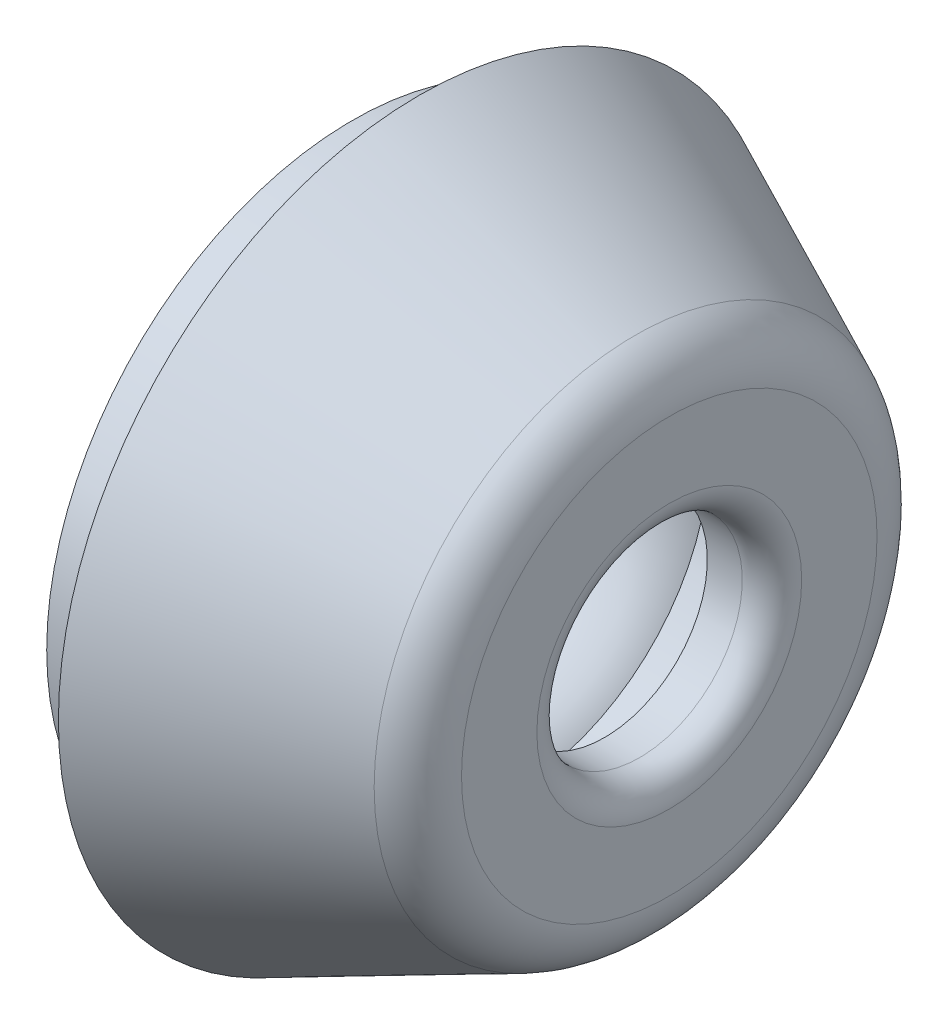
SolidWorks part; units mm, degrees
ref_plane "Face" through (0, 0, 0) normal (0, 0, 1) x (1, 0, 0)
ref_plane "Dessus" through (0, 0, 0) normal (0, 1, 0) x (1, 0, 0)
ref_plane "Droite" through (0, 0, 0) normal (1, 0, 0) x (0, 0, -1)
sketch "Esquisse1" plane through (0, 0, 0) normal (0, 0, 1) x (1, 0, 0)
  line L0 (98.1826, 9.8987) -> (98.1826, 15.4534)
  line L1 (81.0486, 0) -> (115.9484, 0) construction
  line L2 (98.1826, 15.4534) -> (101.5582, 15.4534)
  line L3 (101.5582, 15.4534) -> (101.5582, 18.2382)
  line L4 (101.5582, 18.2382) -> (112.4619, 13.1892)
  line L5 (114.1826, 10.4962) -> (114.1826, 6.6895)
  line L6 (112.6826, 5.1895) -> (110.9166, 5.1895)
  line L7 (110.4166, 9.8987) -> (106.2972, 9.8987)
  line L9 (110.9166, 9.3987) -> (110.9166, 5.1895)
  line L10 (99.7155, 9.8987) -> (98.1826, 9.8987)
  arc A0 (110.4166, 9.8987) -> (110.9166, 9.3987) centre (110.4166, 9.3987) cw
  arc A1 (99.7155, 9.8987) -> (106.2972, 9.8987) centre (103.0064, 12.6175) ccw
  arc A2 (114.1826, 6.6895) -> (112.6826, 5.1895) centre (112.6826, 6.6895) cw
  arc A3 (112.4619, 13.1892) -> (114.1826, 10.4962) centre (111.2149, 10.4962) cw
  dimension "D1" = 0.5
  dimension "D2" = 1.5
  dimension "D3" = 16
revolve "Révolution1" add sketch "Esquisse1" angle 360 about L1
